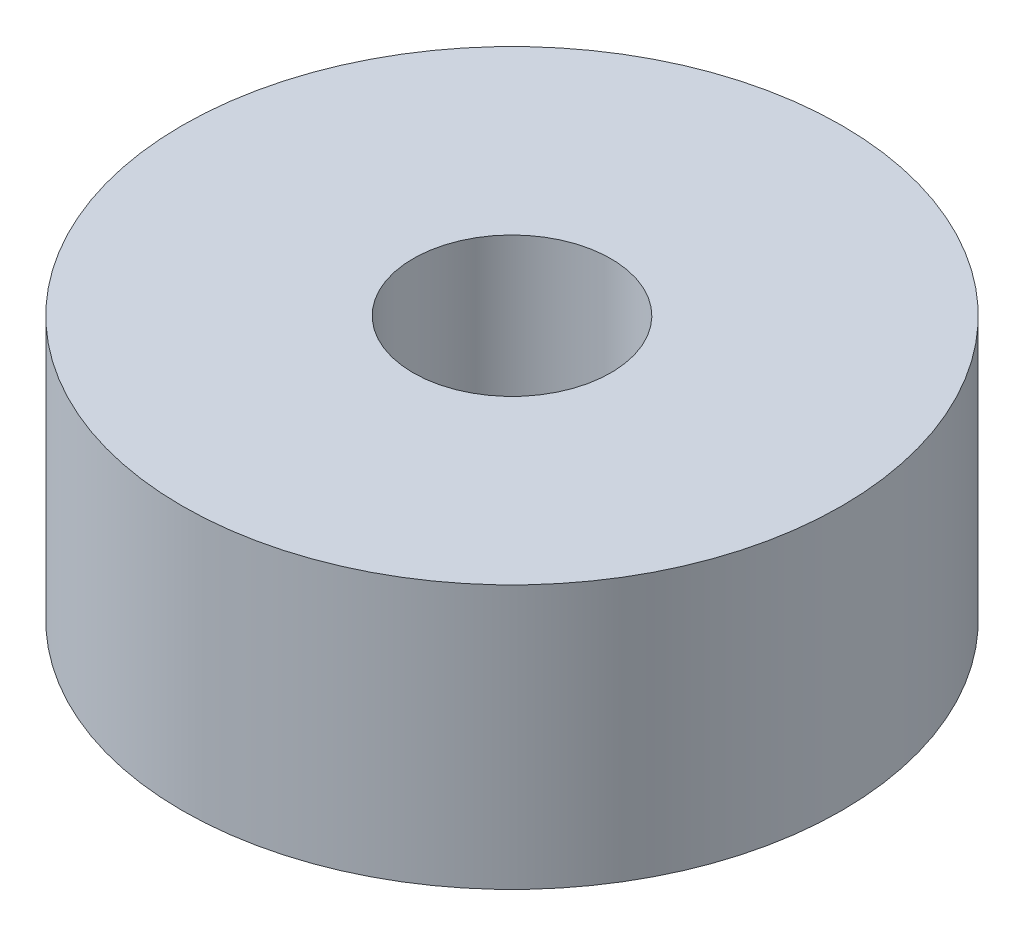
SolidWorks part; units mm, degrees
ref_plane "Front Plane" through (0, 0, 0) normal (0, 0, 1) x (1, 0, 0)
ref_plane "Top Plane" through (0, 0, 0) normal (0, 1, 0) x (1, 0, 0)
ref_plane "Right Plane" through (0, 0, 0) normal (1, 0, 0) x (0, 0, -1)
sketch "Sketch1" plane through (0, 0, 0) normal (0, 1, 0) x (1, 0, 0)
  circle A0 centre (0, 0) radius 63.5
  circle A1 centre (0, 0) radius 19.05
  dimension "D1" = 127
  dimension "D2" = 38.1
extrude "Boss-Extrude1" add sketch "Sketch1" along normal mid plane 50.8
